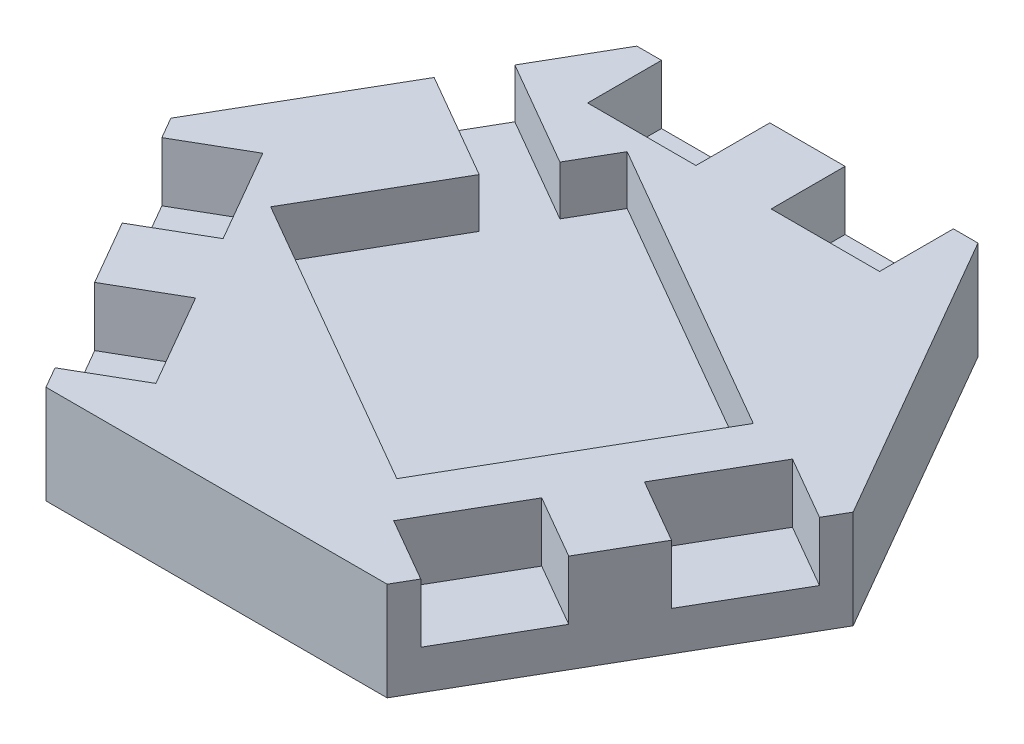
SolidWorks part; units mm, degrees
ref_plane "Front Plane" through (0, 0, 0) normal (0, 0, 1) x (1, 0, 0)
ref_plane "Top Plane" through (0, 0, 0) normal (0, 1, 0) x (1, 0, 0)
ref_plane "Right Plane" through (0, 0, 0) normal (1, 0, 0) x (0, 0, -1)
sketch "Sketch1" plane through (0, 0, 0) normal (0, 1, 0) x (1, 0, 0)
  line L0 (0, 0) -> (39.7226, 0) construction
  line L1 (0, 0) -> (0, 31.3322) construction
  line L3 (69.282, 0) -> (34.641, 60)
  line L4 (34.641, 60) -> (-34.641, 60)
  line L5 (-34.641, 60) -> (-69.282, 0)
  line L6 (-69.282, 0) -> (-34.641, -60)
  line L7 (-34.641, -60) -> (34.641, -60)
  line L8 (34.641, -60) -> (69.282, 0)
  circle A1 centre (0, 0) radius 60 construction
  dimension "D1" = 120
extrude "Boss-Extrude1" add sketch "Sketch1" along normal blind 20
sketch "Sketch2" plane through (0, 20, 0) normal (0, 1, 0) x (1, 0, 0)
  line L0 (-29.641, 60) -> (-29.641, 45)
  line L1 (34.641, 60) -> (-34.641, 60) construction
  line L2 (-29.641, 45) -> (-7.641, 45)
  line L3 (-7.641, 45) -> (-7.641, 60)
  line L4 (7.641, 60) -> (7.641, 45)
  line L5 (7.641, 45) -> (29.641, 45)
  line L6 (29.641, 45) -> (29.641, 60)
  line L7 (66.782, -4.3301) -> (53.7917, 3.1699)
  line L8 (53.7917, 3.1699) -> (42.7917, -15.8827)
  line L9 (42.7917, -15.8827) -> (55.782, -23.3827)
  line L10 (48.141, -36.6173) -> (35.1506, -29.1173)
  line L11 (35.1506, -29.1173) -> (24.1506, -48.1699)
  line L12 (24.1506, -48.1699) -> (37.141, -55.6699)
  line L13 (-37.141, -55.6699) -> (-24.1506, -48.1699)
  line L14 (-24.1506, -48.1699) -> (-35.1506, -29.1173)
  line L15 (-35.1506, -29.1173) -> (-48.141, -36.6173)
  line L16 (-55.782, -23.3827) -> (-42.7917, -15.8827)
  line L17 (-42.7917, -15.8827) -> (-53.7917, 3.1699)
  line L18 (-53.7917, 3.1699) -> (-66.782, -4.3301)
  line L19 (-29.641, 60) -> (-7.641, 60)
  line L20 (7.641, 60) -> (29.641, 60)
  line L21 (66.782, -4.3301) -> (55.782, -23.3827)
  line L22 (48.141, -36.6173) -> (37.141, -55.6699)
  line L23 (-48.141, -36.6173) -> (-37.141, -55.6699)
  line L24 (-66.782, -4.3301) -> (-55.782, -23.3827)
  point P10 (-7.641, 52.5)
  point P11 (29.641, 52.5)
  dimension "D1" = 5
  dimension "D2" = 5
  dimension "D3" = 22
  dimension "D4" = 22
  dimension "D5" = 15
  dimension "D6" = 15
  dimension "D7" = 3
extrude "Cut-Extrude1" cut sketch "Sketch2" against normal blind 12
sketch "Sketch3" plane through (0, 20, 0) normal (0, 1, 0) x (1, 0, 0)
  line L0 (0, 0) -> (-51.9615, 30) construction
  line L1 (-43.5609, -5.4497) -> (17.0609, -40.4497)
  line L2 (-0.0025, 0.0015) -> (34.6385, 60.0015)
  line L3 (-43.5609, -5.4497) -> (-17.0609, 40.4497)
  line L4 (17.0609, -40.4497) -> (43.5609, 5.4497)
  line L5 (-17.0609, 40.4497) -> (43.5609, 5.4497)
  line L6 (-43.5609, -5.4497) -> (43.5609, 5.4497) construction
  line L7 (17.0609, -40.4497) -> (-17.0609, 40.4497) construction
  line L8 (-22.0609, 31.7894) -> (-28.0609, 21.3971)
  line L9 (-22.0609, 31.7894) -> (-43.7115, 44.2894)
  line L10 (-28.0609, 21.3971) -> (-49.7115, 33.8971)
  line L11 (-43.7115, 44.2894) -> (-49.7115, 33.8971)
  line L12 (-34.641, 60) -> (-69.282, 0) construction
  point P4 (0, 0)
  line M19 (-34.641, 60) -> (-69.282, 0)
  dimension "D1" = 70
  dimension "D2" = 53
  dimension "D3" = 10
  dimension "D4" = 12
extrude "Cut-Extrude2" cut sketch "Sketch3" against normal blind 10 and the other way through all contours L5 L3 L1 L2 | L5 L2 L1 L4 | L10 L3 L9 M19
equation "\"D2@Sketch2\"=\"D1@Sketch2\""
equation "\"D4@Sketch2\"=\"D3@Sketch2\""
equation "\"D6@Sketch2\"=\"D5@Sketch2\""
